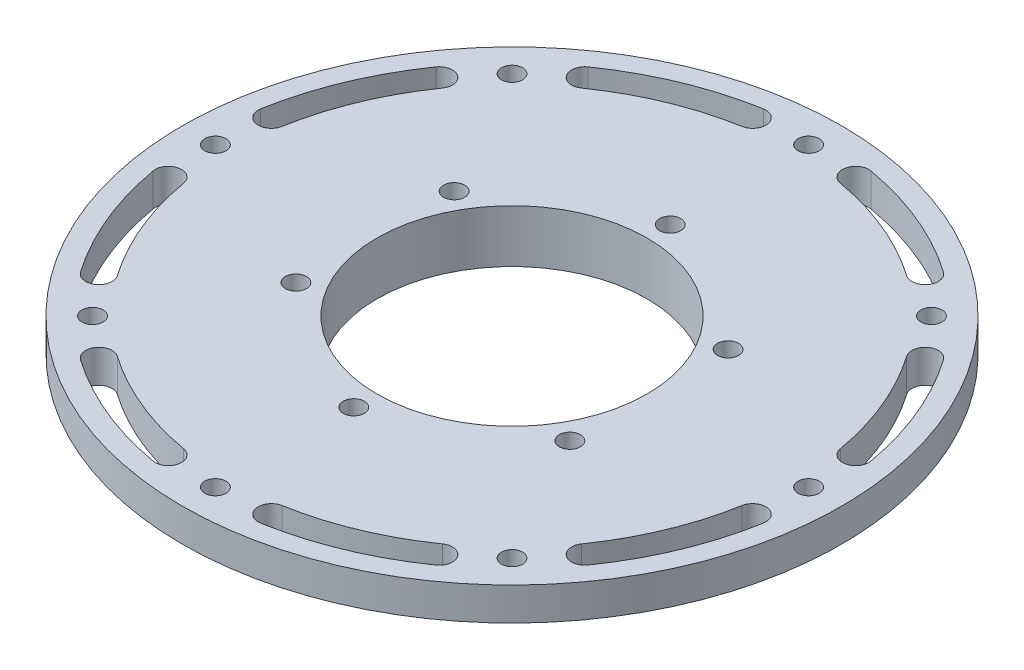
SolidWorks part; units mm, degrees
material "氧化铝"
ref_plane "前视基准面" through (0, 0, 0) normal (0, 0, 1) x (1, 0, 0)
ref_plane "上视基准面" through (0, 0, 0) normal (0, 1, 0) x (1, 0, 0)
ref_plane "右视基准面" through (0, 0, 0) normal (1, 0, 0) x (0, 0, -1)
sketch "草图1" plane through (0, 0, 0) normal (0, 1, 0) x (1, 0, 0)
  circle A0 centre (0, 0) radius 20.5
  dimension "D1" = 41
extrude "凸台-拉伸1" add sketch "草图1" along normal blind 7
sketch "草图2" plane through (0, 7, 0) normal (0, 1, 0) x (1, 0, 0)
  circle A0 centre (0, 0) radius 50
  dimension "D1" = 100
extrude "凸台-拉伸2" add sketch "草图2" along normal blind 8
sketch "草图3" plane through (0, 0, 0) normal (0, -1, 0) x (1, 0, 0)
  circle A0 centre (0, 0) radius 16.5
  dimension "D1" = 33
extrude "切除-拉伸1" cut sketch "草图3" against normal up to next
sketch "草图4" plane through (0, 7, 0) normal (0, -1, 0) x (1, 0, 0)
  circle A0 centre (0, 24) radius 1.6
  dimension "D2" = 3.2
  dimension "D1" = 24
extrude "切除-拉伸2" cut sketch "草图4" against normal up to next
pattern_circular "阵列(圆周)1" count 6 over 360 about axis through (0, 0, 0) along (0, 1, 0) of "切除-拉伸2"
sketch "草图6" plane through (0, 7, 0) normal (0, -1, 0) x (1, 0, 0)
  circle A0 centre (0, 0) radius 27.5
  circle A1 centre (0, 0) radius 50
  circle A2 centre (0, 0) radius 50 construction
  dimension "D1" = 55
extrude "切除-拉伸3" cut sketch "草图6" against normal blind 3
sketch "草图7" plane through (0, 15, 0) normal (0, 1, 0) x (1, 0, 0)
  line L0 (0, -22.1082) -> (0, 94.9747) construction
  circle A0 centre (0, 45) radius 1.6
  dimension "D2" = 3.2
  dimension "D1" = 45
extrude "切除-拉伸4" cut sketch "草图7" against normal up to next
pattern_circular "阵列(圆周)2" count 8 over 360 about axis through (0, 0, 0) along (0, 1, 0) of "切除-拉伸4"
sketch "草图9" plane through (0, 10, 0) normal (0, -1, 0) x (1, 0, 0)
  line L0 (-31.8198, 31.8198) -> (0, 0) construction
  line L1 (0, 0) -> (0, 45) construction
  line L2 (-25.8109, 36.8618) -> (0, 0) construction
  line L3 (0, 0) -> (-7.8142, 44.3163) construction
  arc A0 (-7.4669, 42.3467) -> (-24.6638, 35.2235) centre (0, 0) ccw
  circle A2 centre (0, 0) radius 45 construction
  arc A4 (-26.9581, 38.5001) -> (-24.6638, 35.2235) centre (-25.8109, 36.8618) ccw
  arc A6 (-7.4669, 42.3467) -> (-8.1615, 46.286) centre (-7.8142, 44.3163) ccw
  arc A7 (-8.1615, 46.286) -> (-26.9581, 38.5001) centre (0, 0) ccw
  dimension "D1" = 43
  dimension "D2" = 47
  dimension "D3" = 10
  dimension "D4" = 10
extrude "切除-拉伸5" cut sketch "草图9" against normal up to next
pattern_circular "阵列(圆周)3" count 8 over 360 about axis through (0, 0, 0) along (0, 1, 0) of "切除-拉伸5"
sketch "草图11" plane through (0, 0, 0) normal (0, -1, 0) x (1, 0, 0)
  circle A1 centre (0, 0) radius 20.5
  circle A2 centre (0, 0) radius 20.5
  dimension "D1" = 0
extrude "凸台-拉伸3" add sketch "草图11" against normal blind 4
sketch "草图12" plane through (0, 4, 0) normal (0, 1, 0) x (1, 0, 0)
  circle A0 centre (0, 0) radius 11.5 construction
  circle A1 centre (0, 11.5) radius 2.025
  circle A2 centre (11.5, 0) radius 2.025
  circle A3 centre (0, -11.5) radius 2.025
  circle A4 centre (-11.5, 0) radius 2.025
  point P14 (0, 0)
  dimension "D1" = 23
  dimension "D2" = 4.05
  dimension "D3" = 4
extrude "切除-拉伸6" cut sketch "草图12" against normal through all
sketch "草图13" plane through (0, 0, 0) normal (0, -1, 0) x (1, 0, 0)
  circle A0 centre (0, 0) radius 5
  dimension "D1" = 10
extrude "切除-拉伸7" cut sketch "草图13" against normal through all
sketch "草图14" plane through (0, 0, 0) normal (0, -1, 0) x (1, 0, 0)
  circle A0 centre (0, 0) radius 20.5
extrude "切除-拉伸8" cut sketch "草图14" against normal through all
